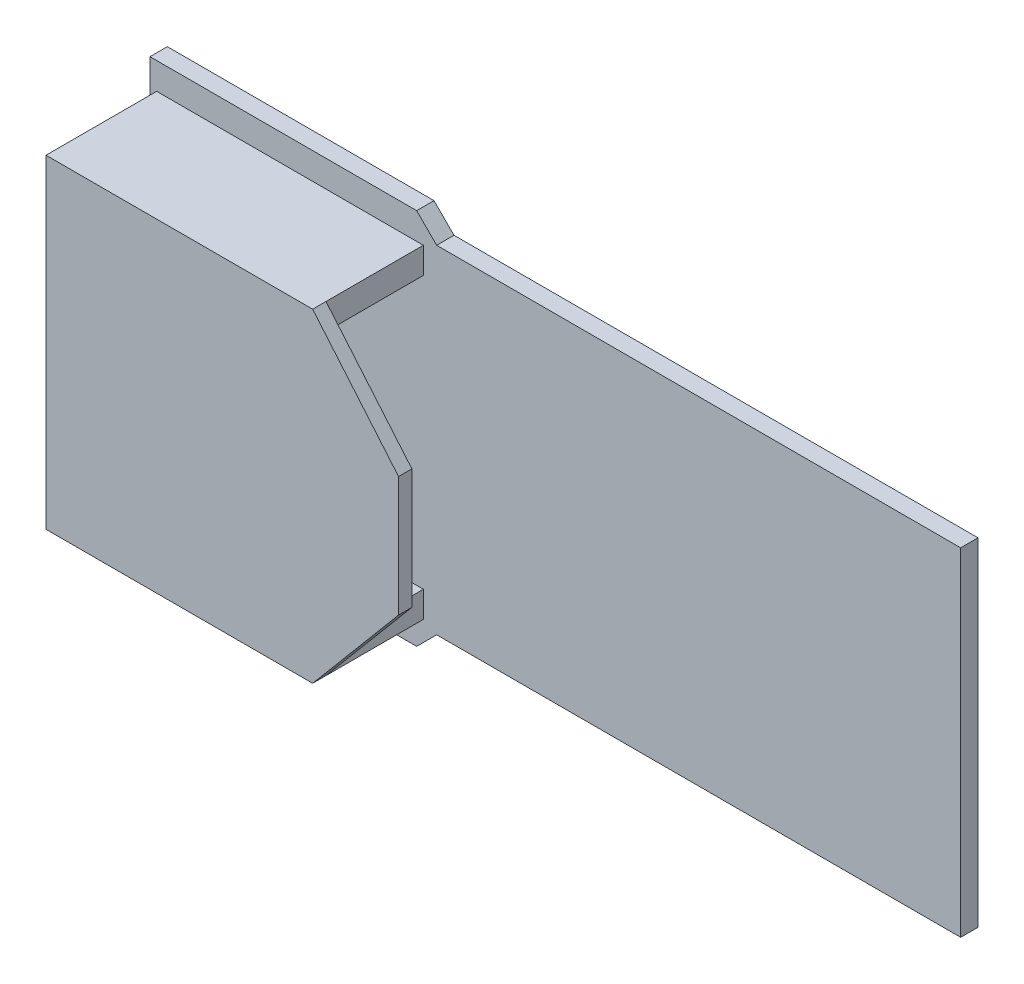
SolidWorks part; units mm, degrees
ref_plane "Plan de face" through (0, 0, 0) normal (0, 0, 1) x (1, 0, 0)
ref_plane "Plan de dessus" through (0, 0, 0) normal (0, 1, 0) x (1, 0, 0)
ref_plane "Plan de droite" through (0, 0, 0) normal (1, 0, 0) x (0, 0, -1)
sketch "Esquisse1" plane through (0, 0, 0) normal (0, 0, 1) x (1, 0, 0)
  line L0 (0, 0) -> (20.7071, 0) construction
  line L1 (0, -14.15) -> (0, 14.15)
  line L2 (0, 14.15) -> (20, 14.15)
  line L3 (0, -14.15) -> (20, -14.15)
  line L4 (20, 14.15) -> (21.5, 12.65)
  line L5 (20, -14.15) -> (21.5, -12.65)
  line L6 (21.5, 12.65) -> (60.8, 12.65)
  line L7 (21.5, -12.65) -> (60.8, -12.65)
  line L8 (60.8, 12.65) -> (60.8, -12.65)
  point P12 (60.8, 0)
  point P14 (6.5, 0)
  dimension "D1" = 60.8
  dimension "D2" = 25.3
  dimension "D3" = 28.3
  dimension "D4" = 135
  dimension "D6" = 20
extrude "Boss.-Extru.1" add sketch "Esquisse1" along normal blind 1.3
sketch "Esquisse2" plane through (0, 0, 0) normal (0, 0, -1) x (-1, 0, 0)
  line L0 (0, 14.15) -> (0, -14.15) construction
  line L6 (0, 8.15) -> (-8, 8.15)
  line L7 (0, 8.15) -> (0, 1.15)
  line L8 (0, 1.15) -> (-8, 1.15)
  line L9 (-8, 8.15) -> (-8, 1.15)
  line L10 (-20, 14.15) -> (0, 14.15) construction
  dimension "D3" = 6
  dimension "D4" = 7
  dimension "D6" = 8
extrude "Boss.-Extru.3" add sketch "Esquisse2" along normal blind 4 contours L8 L9 L6 L7
sketch "Esquisse5" plane through (0, 0, 0) normal (0, 0, -1) x (-1, 0, 0)
  line L1 (0, -10.15) -> (-5, -10.15)
  line L2 (0, -10.15) -> (0, -2.15)
  line L3 (0, -2.15) -> (-5, -2.15)
  line L4 (-5, -10.15) -> (-5, -2.15)
  line L6 (0, 1.15) -> (0, -14.15) construction
  line L7 (0, -14.15) -> (-20, -14.15) construction
  dimension "D1" = 4
  dimension "D2" = 8
  dimension "D5" = 5
extrude "Boss.-Extru.4" add sketch "Esquisse5" along normal blind 6 contours L1 L4 L3 L2
sketch "Esquisse6" plane through (0, 0, 0) normal (-1, 0, 0) x (0, 0, 1)
  line L0 (-4, 8.15) -> (-4, 1.15) construction
  line L1 (-3.5, 1.65) -> (-0.5, 1.65)
  line L2 (-3.5, 1.65) -> (-3.5, 7.65)
  line L3 (-3.5, 7.65) -> (-0.5, 7.65)
  line L4 (-0.5, 1.65) -> (-0.5, 7.65)
  line L5 (-3.5, 1.65) -> (-0.5, 7.65) construction
  line L6 (-3.5, 7.65) -> (-0.5, 1.65) construction
  line L13 (-4, 8.15) -> (0, 8.15) construction
  line L14 (0, 14.15) -> (0, 8.15) construction
  line L15 (-4, 1.15) -> (0, 1.15) construction
  point P0 (-2, 4.65)
  dimension "D1" = 0.5
  dimension "D2" = 0.5
  dimension "D3" = 0.5
  dimension "D4" = 0.5
extrude "Enlèv. mat.-Extru.1" cut sketch "Esquisse6" against normal blind 7
sketch "Esquisse7" plane through (0, 0, 0) normal (-1, 0, 0) x (0, 0, 1)
  line L0 (-5.5, -9.65) -> (-0.5, -9.65)
  line L1 (-5.5, -9.65) -> (-5.5, -2.65)
  line L2 (-5.5, -2.65) -> (-0.5, -2.65)
  line L3 (-0.5, -9.65) -> (-0.5, -2.65)
  line L4 (-5.5, -9.65) -> (-0.5, -2.65) construction
  line L5 (-5.5, -2.65) -> (-0.5, -9.65) construction
  line L6 (-6, -10.15) -> (0, -10.15) construction
  line L7 (-6, -10.15) -> (-6, -2.15) construction
  line L8 (-6, -2.15) -> (0, -2.15) construction
  line L9 (0, 1.15) -> (0, -2.15) construction
  point P0 (-3, -6.15)
  dimension "D1" = 0.5
  dimension "D2" = 0.5
  dimension "D3" = 0.5
  dimension "D4" = 0.5
extrude "Enlèv. mat.-Extru.2" cut sketch "Esquisse7" against normal blind 4 contours L2 L3 L0 L1
sketch "Esquisse8" plane through (0, 0, 1.3) normal (0, 0, 1) x (1, 0, 0)
  line L0 (20, 14.15) -> (0, 14.15) construction
  line L1 (0.5, 10.1908) -> (20.5, 10.1908)
  line L2 (0.5, 10.1908) -> (0.5, 12.15)
  line L3 (0.5, 12.15) -> (20.5, 12.15)
  line L4 (20.5, 10.1908) -> (20.5, 12.15)
  line L5 (0, 14.15) -> (0, -14.15) construction
  line L6 (0, 0) -> (20.5, 0) construction
  line L7 (0.5, -10.1908) -> (20.5, -10.1908)
  line L8 (0.5, -10.1908) -> (0.5, -12.15)
  line L9 (0.5, -12.15) -> (20.5, -12.15)
  line L10 (20.5, -10.1908) -> (20.5, -12.15)
  dimension "D1" = 2
  dimension "D2" = 0.5
  dimension "D3" = 20
  dimension "D4" = 20
extrude "Boss.-Extru.5" add sketch "Esquisse8" along normal blind 7.3
sketch "Esquisse10" plane through (0, 0, 8.6) normal (0, 0, 1) x (1, 0, 0)
  line L0 (0, 0) -> (17.0417, 0) construction
  line L1 (0.5, 12.15) -> (0.5, -12.15)
  line L2 (0.5, 12.15) -> (20.5, 12.15)
  line L3 (0.5, -12.15) -> (20.5, -12.15)
  line L4 (20.5, 12.15) -> (26.9403, 4.5)
  line L5 (20.5, -12.15) -> (26.9403, -4.5)
  line L6 (26.9403, 4.5) -> (26.9403, -4.5)
  point P7 (0.5, 0)
  point P12 (26.9403, 0)
  dimension "D1" = 9
  dimension "D2" = 10
  dimension "D3" = 10
extrude "Boss.-Extru.6" add sketch "Esquisse10" along normal blind 1
